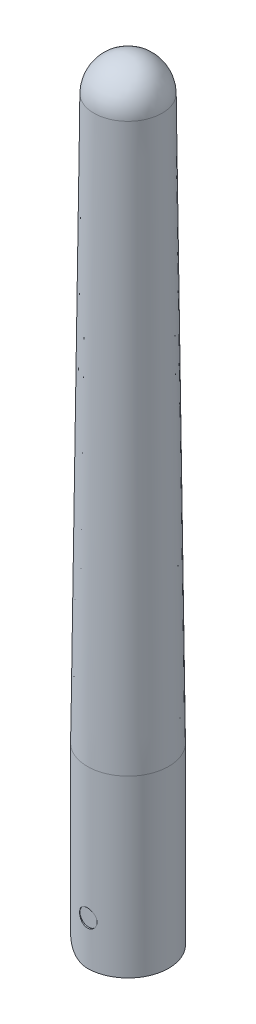
SolidWorks part; units mm, degrees
ref_plane "Front Plane" through (0, 0, 0) normal (0, 0, 1) x (1, 0, 0)
ref_plane "Top Plane" through (0, 0, 0) normal (0, 1, 0) x (1, 0, 0)
ref_plane "Right Plane" through (0, 0, 0) normal (1, 0, 0) x (0, 0, -1)
sketch "Sketch1" plane through (0, 0, 0) normal (0, 0, 1) x (1, 0, 0)
  line L0 (0, 0) -> (0, 88.2)
  line L1 (0, 0) -> (0, -20) construction
  line L2 (-3.8997, 84.3455) -> (-4.65, 20)
  line L3 (-4.65, 20) -> (-4.65, 0)
  line L4 (-4.65, 0) -> (0, 0)
  line L5 (0, 0) -> (4.65, 0) construction
  arc A0 (0, 88.2) -> (-3.8997, 84.3455) centre (0, 84.3) ccw
  dimension "D5" = 3.9
  dimension "D1" = 108.2
  dimension "D2" = 20
  dimension "D3" = 40
  dimension "D4" = 9.3
revolve "Revolve1" add sketch "Sketch1" angle 360 about L0
sketch "Sketch2" plane through (0, 0, 0) normal (0, 0, 1) x (1, 0, 0)
  line L0 (0, 5) -> (0, 0) construction
  circle A0 centre (0, 5) radius 1
  dimension "D2" = 2
  dimension "D1" = 5
extrude "Cut-Extrude1" cut sketch "Sketch2" against normal mid plane 10
sketch "Sketch3" plane through (0, 0, 0) normal (0, 0, 1) x (1, 0, 0)
  line L0 (3, 0) -> (3, 5)
  line L1 (3, 0) -> (-4.65, 0)
  line L2 (-4.65, 0) -> (-4.65, 8)
  line L3 (-4.65, 8) -> (0, 8)
  line L4 (0, 0) -> (0, 8) construction
  line L5 (-4.65, 20) -> (-4.65, 0) construction
  arc A0 (3, 5) -> (0, 8) centre (0, 5) ccw
  circle A1 centre (0, 5) radius 1 construction
  dimension "D1" = 3
extrude "Cut-Extrude2" cut sketch "Sketch3" against normal mid plane 5
sketch "Sketch4" plane through (0, 0, 0) normal (0, 0, 1) x (1, 0, 0)
  line L0 (-5, 5) -> (-8, 5)
  line L1 (-8, 5) -> (-8, -3)
  line L2 (-8, -3) -> (0, -3)
  line L3 (0, -3) -> (0, 0)
  arc A0 (0, 0) -> (-5, 5) centre (0, 5) cw
  dimension "D1" = 8
extrude "Cut-Extrude3" cut sketch "Sketch4" against normal mid plane 10
sketch "Sketch5" plane through (0, 0, 0) normal (0, 0, 1) x (1, 0, 0)
  circle A0 centre (0, 5) radius 1
  circle A1 centre (0, 5) radius 1 construction
extrude "Boss-Extrude1" add sketch "Sketch5" along normal mid plane 9
